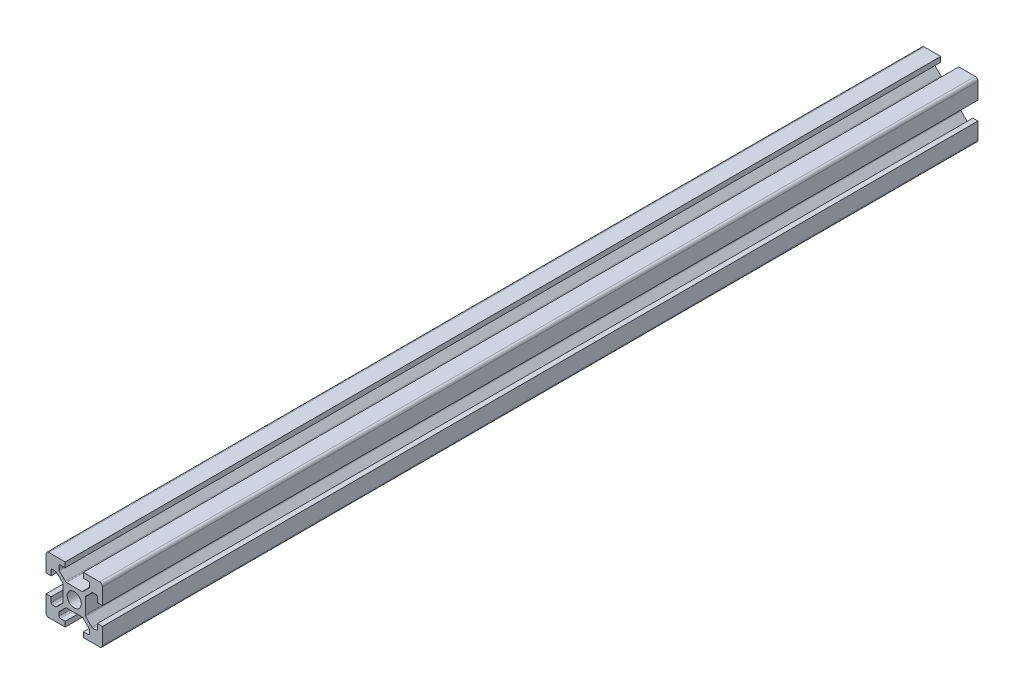
SolidWorks part; units mm, degrees
material "1060 Alloy"
ref_plane "Front Plane" through (0, 0, 0) normal (0, 0, 1) x (1, 0, 0)
ref_plane "Top Plane" through (0, 0, 0) normal (0, 1, 0) x (1, 0, 0)
ref_plane "Right Plane" through (0, 0, 0) normal (1, 0, 0) x (0, 0, -1)
sketch "Sketch1" plane through (0, 0, 0) normal (0, 0, 1) x (1, 0, 0)
  line L0 (20, 0) -> (-8.059, 28.059) construction
  line L1 (0, 0) -> (6.8, 0)
  line L2 (0, 0) -> (0, 6.8)
  line L3 (0, 20) -> (6.8, 20)
  line L4 (20, 0) -> (20, 6.8)
  line L5 (6.8, 20) -> (6.8, 18.2)
  line L6 (20, 20) -> (8.2322, 8.2322) construction
  line L7 (12.95, 6.1) -> (7.05, 6.1)
  line L8 (13.9, 7.05) -> (13.9, 12.95)
  line L9 (12.95, 13.9) -> (7.05, 13.9)
  line L10 (6.1, 7.05) -> (6.1, 12.95)
  line L11 (13.9, 6.1) -> (6.1, 13.9) construction
  line L12 (13.9, 13.9) -> (6.1, 6.1) construction
  line L13 (4.55, 16.4) -> (7.05, 13.9)
  line L14 (13.2, 18.2) -> (13.2, 20)
  line L15 (1.8, 6.8) -> (0, 6.8)
  line L16 (0, 13.2) -> (0, 20)
  line L17 (0, 13.2) -> (1.8, 13.2)
  line L18 (10, 10) -> (10, 13.9) construction
  line L19 (16.4, 4.55) -> (13.9, 7.05)
  line L20 (4.55, 16.4) -> (4.55, 18.2)
  line L21 (4.55, 18.2) -> (6.8, 18.2)
  line L22 (13.2, 18.2) -> (15.45, 18.2)
  line L23 (15.45, 18.2) -> (15.45, 16.4)
  line L24 (15.45, 16.4) -> (12.95, 13.9)
  line L25 (16.4, 4.55) -> (18.2, 4.55)
  line L26 (18.2, 4.55) -> (18.2, 6.8)
  line L27 (20, 6.8) -> (18.2, 6.8)
  line L28 (18.2, 13.2) -> (20, 13.2)
  line L29 (18.2, 13.2) -> (18.2, 15.45)
  line L30 (18.2, 15.45) -> (16.4, 15.45)
  line L31 (16.4, 15.45) -> (13.9, 12.95)
  line L32 (1.8, 4.55) -> (3.6, 4.55)
  line L33 (3.6, 15.45) -> (6.1, 12.95)
  line L34 (3.6, 15.45) -> (1.8, 15.45)
  line L35 (1.8, 15.45) -> (1.8, 13.2)
  line L36 (0, 13.2) -> (1.8, 13.2)
  line L37 (1.8, 6.8) -> (0, 6.8)
  line L38 (3.6, 4.55) -> (6.1, 7.05)
  line L39 (1.8, 6.8) -> (1.8, 4.55)
  line L40 (15.45, 3.6) -> (12.95, 6.1)
  line L41 (4.55, 3.6) -> (7.05, 6.1)
  line L42 (4.55, 1.8) -> (4.55, 3.6)
  line L43 (6.8, 1.8) -> (4.55, 1.8)
  line L44 (6.8, 1.8) -> (6.8, 0)
  line L45 (15.45, 3.6) -> (15.45, 1.8)
  line L46 (15.45, 1.8) -> (13.2, 1.8)
  line L47 (13.2, 0) -> (13.2, 1.8)
  line L48 (13.2, 20) -> (20, 20)
  line L49 (20, 13.2) -> (20, 20)
  line L50 (13.2, 0) -> (20, 0)
  line L51 (6.1, 6.1) -> (-5.5045, -5.5045) construction
  circle A0 centre (10, 10) radius 2.5
  point P25 (10, 16.4)
  point P39 (13.2, 19.1)
  point P46 (0.9, 6.8)
  dimension "D3" = 5
  dimension "D2" = 20
  dimension "D4" = 7.8
  dimension "D5" = 7.8
  dimension "D6" = 6.8
  dimension "D7" = 6.8
  dimension "D8" = 1.8
  dimension "D9" = 10.9
  dimension "D10" = 1.8
  dimension "D11" = 10.9
  dimension "D12" = 20
extrude "Boss-Extrude1" add sketch "Sketch1" along normal blind 310 contours L47 L50 L4 L27 L26 L25 L19 L8 L31 L30 L29 L28 L49 L48 L14 L22 L23 L24 L9 L13 L20 L21 L5 L3 L16 L17 L35 L34 L33 L10 L38 L32 L39 L15 L2 L1 L44 L43 L42 L41 L7 L40 L45 L46 A0
fillet "Fillet1" radius 1 4 edges at (20, 20, 155) (20, 0, 155) (0, 0, 155) (0, 20, 155)
fillet "Fillet2" radius 0.5 6 edges at (4.55, 18.2, 155) (4.55, 16.4, 155) (7.05, 13.9, 155) (15.45, 18.2, 155) (15.45, 16.4, 155) (12.95, 13.9, 155)
fillet "Fillet3" radius 0.5 6 edges at (18.2, 15.45, 155) (16.4, 15.45, 155) (13.9, 12.95, 155) (18.2, 4.55, 155) (13.9, 7.05, 155) (16.4, 4.55, 155)
fillet "Fillet4" radius 0.5 6 edges at (1.8, 15.45, 155) (3.6, 15.45, 155) (6.1, 12.95, 155) (3.6, 4.55, 155) (1.8, 4.55, 155) (6.1, 7.05, 155)
fillet "Fillet5" radius 0.5 6 edges at (7.05, 6.1, 155) (4.55, 3.6, 155) (4.55, 1.8, 155) (15.45, 1.8, 155) (15.45, 3.6, 155) (12.95, 6.1, 155)
